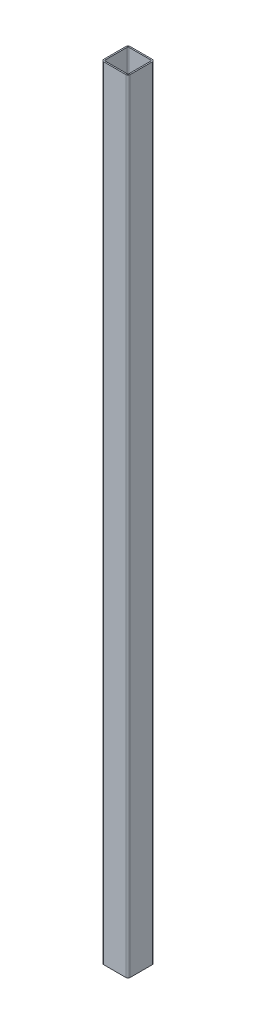
SolidWorks part; units mm, degrees
ref_plane "Front Plane" through (0, 0, 0) normal (0, 0, 1) x (1, 0, 0)
ref_plane "Top Plane" through (0, 0, 0) normal (0, 1, 0) x (1, 0, 0)
ref_plane "Right Plane" through (0, 0, 0) normal (1, 0, 0) x (0, 0, -1)
sketch "Sketch1" plane through (0, 0, 0) normal (0, 1, 0) x (1, 0, 0)
  line L1 (-25, 30) -> (25, 30)
  line L2 (-30, 25) -> (-30, -25)
  line L3 (-25, -30) -> (25, -30)
  line L4 (30, 25) -> (30, -25)
  line L5 (-30, 30) -> (30, -30) construction
  line L6 (-30, -30) -> (30, 30) construction
  arc A0 (30, -25) -> (25, -30) centre (25, -25) cw
  arc A1 (25, 30) -> (30, 25) centre (25, 25) cw
  arc A2 (-25, 30) -> (-30, 25) centre (-25, 25) ccw
  arc A3 (-25, -30) -> (-30, -25) centre (-25, -25) cw
  point P0 (0, 0)
  dimension "D3" = 5
  dimension "D1" = 60
  dimension "D2" = 60
extrude "Extrude-Thin1" add sketch "Sketch1" along normal blind 630 and the other way blind 1143 thin
sketch "Sketch3" plane through (0, 0, 0) normal (1, 0, 0) x (0, 0, -1)
  line L0 (30, 595.359) -> (-30, 630)
  line L1 (0, 55) -> (0, -55) construction
  line L3 (30, 595.359) -> (30, 630)
  line L4 (30, 630) -> (-30, 630)
  point P5 (0, 612.6795)
  dimension "D1" = 60
extrude "Cut-Extrude1" [suppressed] cut sketch "Sketch3" against normal mid plane 86
sketch "Sketch4" plane through (0, 0, 0) normal (0, 0, 1) x (1, 0, 0)
  line L2 (0, -55) -> (0, 55) construction
  line L3 (-25, -1143) -> (25, -1143) construction
  circle A0 centre (0, -1109) radius 5
  circle A1 centre (0, -1069) radius 5
  dimension "D1" = 10
  dimension "D2" = 40
  dimension "D3" = 34
extrude "Cut-Extrude2" [suppressed] cut sketch "Sketch4" along normal through all
